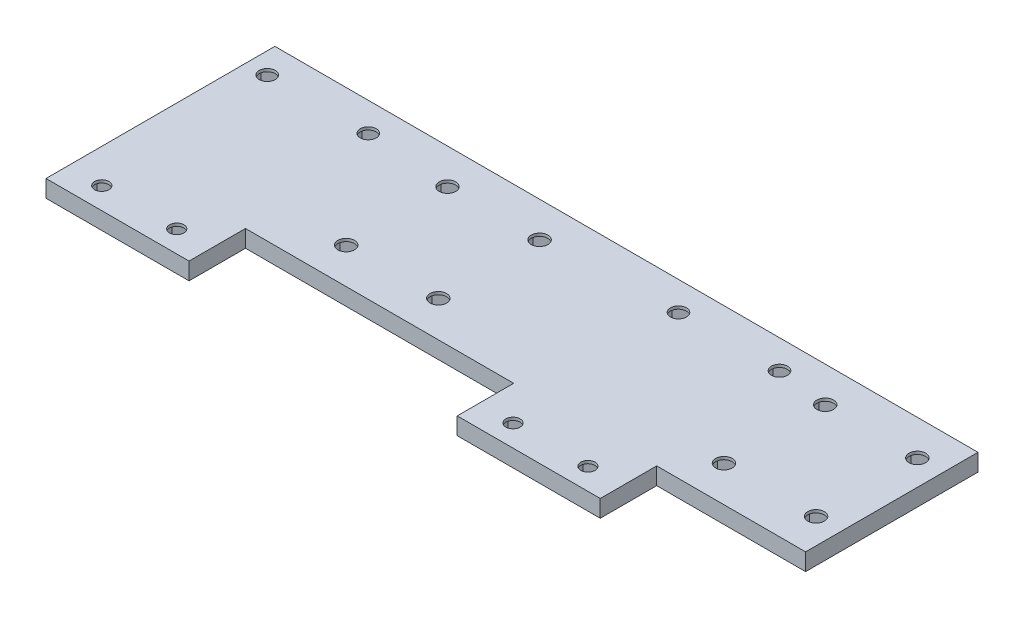
SolidWorks part; units mm, degrees
ref_plane "Front Plane" through (0, 0, 0) normal (0, 0, 1) x (1, 0, 0)
ref_plane "Top Plane" through (0, 0, 0) normal (0, 1, 0) x (1, 0, 0)
ref_plane "Right Plane" through (0, 0, 0) normal (1, 0, 0) x (0, 0, -1)
sketch "Sketch1" plane through (0, 0, 0) normal (0, 1, 0) x (1, 0, 0)
  line L1 (0, 0) -> (140, 0)
  line L2 (0, 0) -> (0, 40)
  line L3 (0, 40) -> (140, 40)
  line L4 (140, 0) -> (140, 40)
  dimension "D1" = 140
  dimension "D2" = 40
extrude "Boss-Extrude1" add sketch "Sketch1" along normal blind 3
sketch "Sketch2" plane through (0, 0, 0) normal (0, -1, 0) x (1, 0, 0)
  circle A0 centre (3.675, -35) radius 1.4
  circle A1 centre (21.325, -35) radius 1.4
  circle A2 centre (3.675, -35) radius 1.4 construction
  circle A3 centre (21.325, -35) radius 1.4 construction
  circle A4 centre (5.95, -3.8) radius 1.25
  circle A5 centre (19.05, -3.8) radius 1.25
  circle A6 centre (36.32, -33.85) radius 1.45
  circle A7 centre (52.42, -33.85) radius 1.45
  circle A8 centre (52.42, -16.15) radius 1.45
  circle A9 centre (36.32, -16.15) radius 1.45
  circle A10 centre (36.32, -16.15) radius 1.45 construction
  circle A11 centre (36.32, -33.85) radius 1.45 construction
  circle A12 centre (52.42, -33.85) radius 1.45 construction
  circle A13 centre (52.42, -16.15) radius 1.45 construction
  circle A14 centre (19.05, -3.8) radius 1.25 construction
  circle A15 centre (5.95, -3.8) radius 1.25 construction
  circle A16 centre (75.545, -35) radius 1.4
  circle A17 centre (75.545, -35) radius 1.4 construction
  circle A18 centre (93.195, -35) radius 1.4
  circle A19 centre (93.195, -35) radius 1.4 construction
  circle A20 centre (77.82, -3.8) radius 1.25
  circle A21 centre (77.82, -3.8) radius 1.25 construction
  circle A22 centre (90.92, -3.8) radius 1.25
  circle A23 centre (90.92, -3.8) radius 1.25 construction
  circle A24 centre (102.343, -33.85) radius 1.45
  circle A25 centre (102.343, -33.85) radius 1.45 construction
  circle A26 centre (118.443, -33.85) radius 1.45
  circle A27 centre (118.443, -33.85) radius 1.45 construction
  circle A28 centre (102.343, -16.15) radius 1.45
  circle A29 centre (102.343, -16.15) radius 1.45 construction
  circle A30 centre (118.443, -16.15) radius 1.45
  circle A31 centre (118.443, -16.15) radius 1.45 construction
extrude "Cut-Extrude1" cut sketch "Sketch2" against normal through all
sketch "Sketch3" plane through (0, 0, 0) normal (0, -1, 0) x (1, 0, 0)
  line L0 (8, -2.6164) -> (5.95, -1.4329) construction
  line L1 (8, -4.9836) -> (8, -2.6164)
  line L2 (8, -2.6164) -> (5.95, -1.4329)
  line L3 (5.95, -1.4329) -> (3.9, -2.6164)
  line L4 (3.9, -2.6164) -> (3.9, -4.9836)
  line L5 (3.9, -4.9836) -> (5.95, -6.1671)
  line L6 (5.95, -6.1671) -> (8, -4.9836)
  line L7 (21.1, -2.6164) -> (19.05, -1.4329) construction
  line L8 (21.1, -4.9836) -> (21.1, -2.6164)
  line L9 (21.1, -2.6164) -> (19.05, -1.4329)
  line L10 (19.05, -1.4329) -> (17, -2.6164)
  line L11 (17, -2.6164) -> (17, -4.9836)
  line L12 (17, -4.9836) -> (19.05, -6.1671)
  line L13 (19.05, -6.1671) -> (21.1, -4.9836)
  line L14 (6.325, -33.47) -> (3.675, -31.94) construction
  line L15 (6.325, -36.53) -> (6.325, -33.47)
  line L16 (6.325, -33.47) -> (3.675, -31.94)
  line L17 (3.675, -31.94) -> (1.025, -33.47)
  line L18 (1.025, -33.47) -> (1.025, -36.53)
  line L19 (1.025, -36.53) -> (3.675, -38.06)
  line L20 (3.675, -38.06) -> (6.325, -36.53)
  line L21 (23.975, -33.47) -> (21.325, -31.94) construction
  line L22 (21.325, -38.06) -> (23.975, -36.53)
  line L23 (23.975, -36.53) -> (23.975, -33.47)
  line L24 (23.975, -33.47) -> (21.325, -31.94)
  line L25 (21.325, -31.94) -> (18.675, -33.47)
  line L26 (18.675, -33.47) -> (18.675, -36.53)
  line L27 (18.675, -36.53) -> (21.325, -38.06)
  line L28 (38.97, -14.62) -> (36.32, -13.09) construction
  line L29 (38.97, -17.68) -> (38.97, -14.62)
  line L30 (38.97, -14.62) -> (36.32, -13.09)
  line L31 (36.32, -13.09) -> (33.67, -14.62)
  line L32 (33.67, -14.62) -> (33.67, -17.68)
  line L33 (33.67, -17.68) -> (36.32, -19.21)
  line L34 (36.32, -19.21) -> (38.97, -17.68)
  line L35 (55.07, -14.62) -> (52.42, -13.09) construction
  line L36 (52.42, -19.21) -> (55.07, -17.68)
  line L37 (55.07, -17.68) -> (55.07, -14.62)
  line L38 (55.07, -14.62) -> (52.42, -13.09)
  line L39 (52.42, -13.09) -> (49.77, -14.62)
  line L40 (49.77, -14.62) -> (49.77, -17.68)
  line L41 (49.77, -17.68) -> (52.42, -19.21)
  line L43 (38.97, -35.38) -> (38.97, -32.32)
  line L44 (38.97, -32.32) -> (36.32, -30.79)
  line L45 (36.32, -30.79) -> (33.67, -32.32)
  line L46 (33.67, -32.32) -> (33.67, -35.38)
  line L47 (33.67, -35.38) -> (36.32, -36.91)
  line L48 (36.32, -36.91) -> (38.97, -35.38)
  line L49 (55.07, -35.38) -> (55.07, -32.32)
  line L50 (55.07, -32.32) -> (52.42, -30.79)
  line L51 (52.42, -30.79) -> (49.77, -32.32)
  line L52 (49.77, -32.32) -> (49.77, -35.38)
  line L53 (49.77, -35.38) -> (52.42, -36.91)
  line L54 (52.42, -36.91) -> (55.07, -35.38)
  line L55 (78.195, -33.47) -> (75.545, -31.94)
  line L56 (75.545, -31.94) -> (72.895, -33.47)
  line L57 (72.895, -33.47) -> (72.895, -36.53)
  line L58 (72.895, -36.53) -> (75.545, -38.06)
  line L59 (75.545, -38.06) -> (78.195, -36.53)
  line L60 (78.195, -36.53) -> (78.195, -33.47)
  line L61 (95.845, -36.53) -> (95.845, -33.47)
  line L62 (95.845, -33.47) -> (93.195, -31.94)
  line L63 (93.195, -31.94) -> (90.545, -33.47)
  line L64 (90.545, -33.47) -> (90.545, -36.53)
  line L65 (90.545, -36.53) -> (93.195, -38.06)
  line L66 (93.195, -38.06) -> (95.845, -36.53)
  line L67 (90.92, -6.1671) -> (92.97, -4.9836)
  line L68 (92.97, -4.9836) -> (92.97, -2.6164)
  line L69 (92.97, -2.6164) -> (90.92, -1.4329)
  line L70 (90.92, -1.4329) -> (88.87, -2.6164)
  line L71 (88.87, -2.6164) -> (88.87, -4.9836)
  line L72 (88.87, -4.9836) -> (90.92, -6.1671)
  line L73 (33.67, -35.38) -> (36.32, -36.91) construction
  line L74 (52.42, -36.91) -> (55.07, -35.38) construction
  line L75 (77.82, -6.1671) -> (79.87, -4.9836) construction
  line L76 (121.093, -14.62) -> (118.443, -13.09) construction
  line L77 (79.87, -4.9836) -> (79.87, -2.6164)
  line L78 (79.87, -2.6164) -> (77.82, -1.4329)
  line L79 (90.92, -1.4329) -> (88.87, -2.6164) construction
  line L80 (72.895, -33.47) -> (72.895, -36.53) construction
  line L81 (93.195, -38.06) -> (95.845, -36.53) construction
  line L82 (77.82, -1.4329) -> (75.77, -2.6164)
  line L83 (75.77, -2.6164) -> (75.77, -4.9836)
  line L84 (75.77, -4.9836) -> (77.82, -6.1671)
  line L85 (77.82, -6.1671) -> (79.87, -4.9836)
  line L86 (118.443, -30.79) -> (115.793, -32.32)
  line L87 (115.793, -32.32) -> (115.793, -35.38)
  line L88 (115.793, -35.38) -> (118.443, -36.91)
  line L89 (118.443, -36.91) -> (121.093, -35.38)
  line L90 (121.093, -35.38) -> (121.093, -32.32)
  line L91 (121.093, -32.32) -> (118.443, -30.79)
  line L92 (102.343, -30.79) -> (99.693, -32.32)
  line L93 (99.693, -32.32) -> (99.693, -35.38)
  line L94 (99.693, -35.38) -> (102.343, -36.91)
  line L95 (102.343, -36.91) -> (104.993, -35.38)
  line L96 (104.993, -35.38) -> (104.993, -32.32)
  line L97 (104.993, -32.32) -> (102.343, -30.79)
  line L98 (102.343, -13.09) -> (99.693, -14.62)
  line L99 (99.693, -14.62) -> (99.693, -17.68)
  line L100 (99.693, -17.68) -> (102.343, -19.21)
  line L101 (102.343, -19.21) -> (104.993, -17.68)
  line L102 (104.993, -17.68) -> (104.993, -14.62)
  line L103 (104.993, -14.62) -> (102.343, -13.09)
  line L104 (118.443, -13.09) -> (115.793, -14.62)
  line L105 (115.793, -14.62) -> (115.793, -17.68)
  line L106 (115.793, -17.68) -> (118.443, -19.21)
  line L107 (118.443, -19.21) -> (121.093, -17.68)
  line L108 (121.093, -17.68) -> (121.093, -14.62)
  line L109 (121.093, -14.62) -> (118.443, -13.09)
  line L110 (121.093, -32.32) -> (118.443, -30.79) construction
  line L111 (104.993, -32.32) -> (102.343, -30.79) construction
  line L112 (104.993, -17.68) -> (104.993, -14.62) construction
  circle A0 centre (5.95, -3.8) radius 2.05 construction
  circle A1 centre (19.05, -3.8) radius 2.05 construction
  circle A2 centre (3.675, -35) radius 2.65 construction
  circle A3 centre (21.325, -35) radius 2.65 construction
  circle A4 centre (36.32, -16.15) radius 2.65 construction
  circle A5 centre (52.42, -16.15) radius 2.65 construction
  circle A6 centre (36.32, -33.85) radius 2.65 construction
  circle A7 centre (52.42, -33.85) radius 2.65 construction
  circle A8 centre (75.545, -35) radius 2.65 construction
  circle A9 centre (93.195, -35) radius 2.65 construction
  circle A10 centre (90.92, -3.8) radius 2.05 construction
  circle A11 centre (77.82, -3.8) radius 2.05 construction
  circle A12 centre (118.443, -33.85) radius 2.65 construction
  circle A13 centre (102.343, -33.85) radius 2.65 construction
  circle A14 centre (102.343, -16.15) radius 2.65 construction
  circle A15 centre (118.443, -16.15) radius 2.65 construction
extrude "Cut-Extrude2" cut sketch "Sketch3" against normal blind 2.5
sketch "Sketch4" plane through (0, 3, 0) normal (0, 1, 0) x (1, 0, 0)
  line L0 (103.5745, 12.1715) -> (68.5704, 12.1715)
  line L1 (68.5704, 12.1715) -> (68.5704, 28.835)
  line L2 (68.5704, 28.835) -> (103.5745, 12.1715)
  line L3 (103.5745, 12.1715) -> (103.8352, 12.1815)
  line L4 (32.1243, 12.1715) -> (4.6796, 12.1715)
  line L5 (4.6796, 12.1715) -> (32.1243, 28.835)
  line L6 (32.1243, 28.835) -> (32.1243, 12.1715)
  line L7 (32.1243, 12.1715) -> (32.2586, 12.1131)
extrude "Cut-Extrude3" [suppressed] cut sketch "Sketch4" against normal blind 2 contours L6 L5 L4 | L0 L1 L2
sketch "Sketch5" plane through (0, 3, 0) normal (0, 1, 0) x (1, 0, 0)
  line L0 (25, 0) -> (25, 40) construction
  line L1 (25, 9.8669) -> (71.87, 9.8669)
  line L2 (25, 9.8669) -> (25, 0)
  line L3 (25, 0) -> (71.87, 0)
  line L4 (71.87, 9.8669) -> (71.87, 0)
  line L5 (0, 0) -> (140, 0) construction
  line L6 (96.87, 0) -> (96.87, 40) construction
  line L7 (96.87, 9.8669) -> (122.893, 9.8669)
  line L8 (96.87, 9.8669) -> (96.87, 0)
  line L9 (96.87, 0) -> (140, 0)
  line L10 (140, 9.8669) -> (140, 0)
  line L11 (140, 40) -> (0, 40) construction
  line L12 (122.893, 40) -> (140, 40)
  line L13 (122.893, 40) -> (122.893, 9.8669)
  line L14 (71.87, 40) -> (71.87, 0) construction
  line L15 (140, 40) -> (140, 9.8669)
  line L16 (122.893, 10) -> (122.893, 40) construction
extrude "Cut-Extrude4" cut sketch "Sketch5" against normal through all
